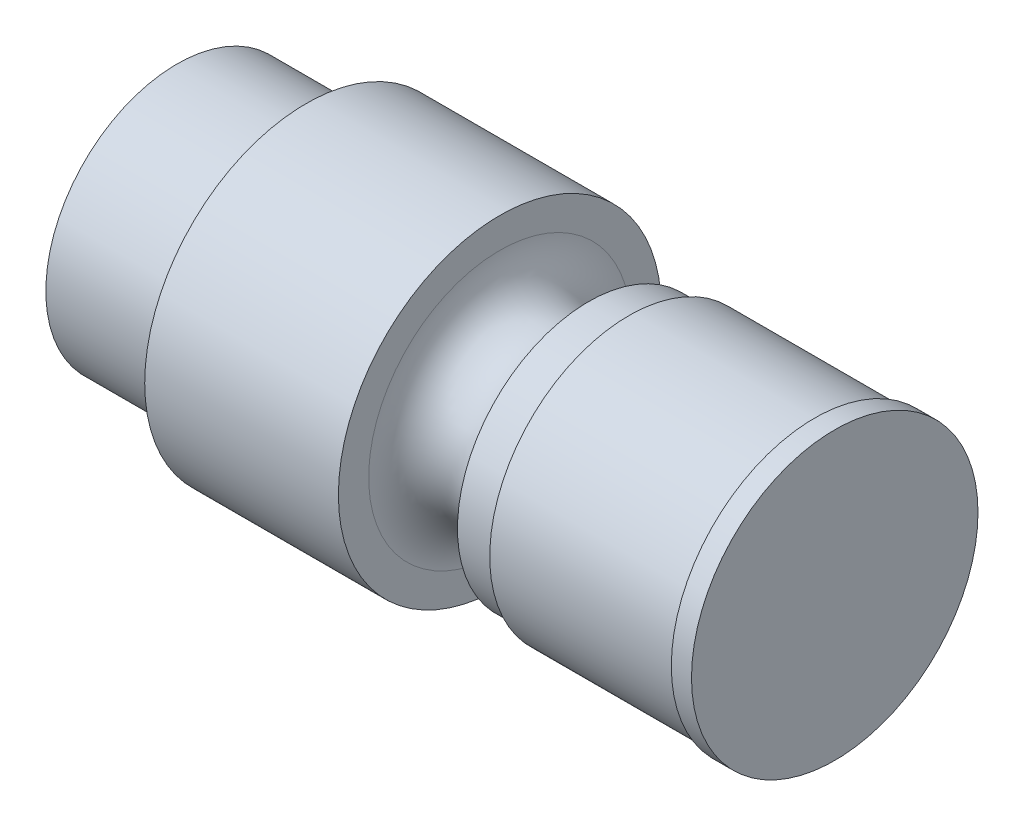
SolidWorks part; units mm, degrees
ref_plane "Front Plane" through (0, 0, 0) normal (0, 0, 1) x (1, 0, 0)
ref_plane "Top Plane" through (0, 0, 0) normal (0, 1, 0) x (1, 0, 0)
ref_plane "Right Plane" through (0, 0, 0) normal (1, 0, 0) x (0, 0, -1)
sketch "Sketch1" plane through (0, 0, 0) normal (0, 0, 1) x (1, 0, 0)
  line L0 (0, 0) -> (32, 0)
  line L1 (32, 0) -> (32, -7.5)
  line L2 (32, -7.5) -> (80, -7.5)
  line L3 (80, -7.5) -> (80, 0)
  line L4 (102, 0) -> (112, 0)
  line L5 (112, 0) -> (112, -2)
  line L6 (112, -2) -> (158, -2)
  line L7 (158, -2) -> (158, -3)
  line L8 (158, -3) -> (163, -3)
  line L9 (0, 0) -> (0, 32.5)
  line L10 (0, 32.5) -> (187.3781, 32.5) construction
  line L11 (163, -3) -> (163, 32.5)
  line L12 (163, 32.5) -> (0, 32.5)
  arc A0 (102, 0) -> (80, 0) centre (91, 0) ccw
revolve "Revolve1" add sketch "Sketch1" angle 360 about L12
